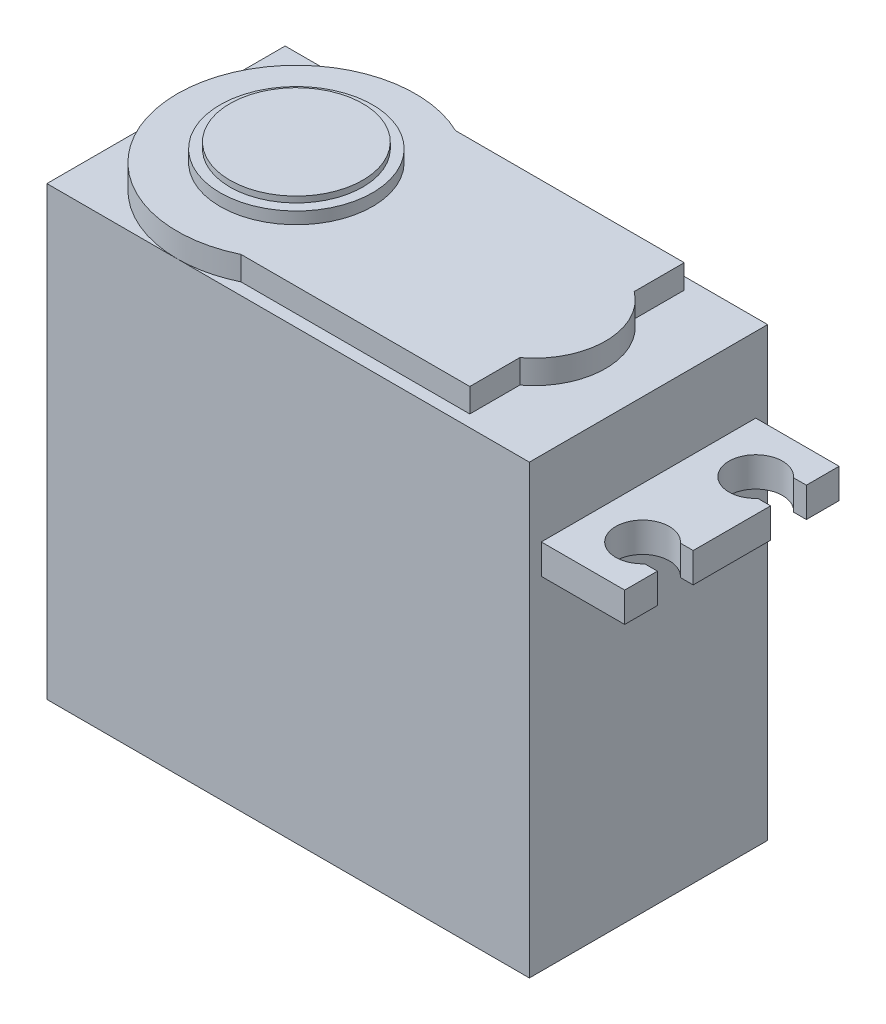
SolidWorks part; units mm, degrees
ref_plane "Front" through (0, 0, 0) normal (0, 0, 1) x (1, 0, 0)
ref_plane "Top" through (0, 0, 0) normal (0, 1, 0) x (1, 0, 0)
ref_plane "Right" through (0, 0, 0) normal (1, 0, 0) x (0, 0, -1)
sketch "Sketch1" plane through (0, 0, 0) normal (0, 1, 0) x (1, 0, 0)
  line L0 (-20.25, 10) -> (20.25, -10) construction
  line L1 (-20.25, -10) -> (20.25, -10)
  line L2 (-20.25, -10) -> (-20.25, 10)
  line L3 (-20.25, 10) -> (20.25, 10)
  line L4 (20.25, -10) -> (20.25, 10)
  line L5 (20.25, 10) -> (-20.25, -10) construction
  dimension "D1" = 20
  dimension "D2" = 40.5
extrude "Boss-Extrude1" add sketch "Sketch1" along normal blind 37.5
sketch "Sketch2" plane through (0, 37.5, 0) normal (0, 1, 0) x (1, 0, 0)
  line L0 (-4.95, -9) -> (14.25, -9)
  line L1 (14.25, -9) -> (14.25, -4.8)
  line L2 (-4.95, 9) -> (14.25, 9)
  line L3 (14.25, 9) -> (14.25, 4.8)
  line L4 (20.25, 10) -> (-20.25, 10) construction
  line L5 (-20.25, -10) -> (20.25, -10) construction
  line L6 (20.25, -10) -> (20.25, 10) construction
  line L7 (20.25, -10) -> (20.25, 10) construction
  arc A0 (-4.95, 9) -> (-4.95, -9) centre (-9.3089, 0) ccw
  arc A1 (14.25, 4.8) -> (14.25, -4.8) centre (10.65, 0) cw
  point P6 (0, 10)
  point P12 (16.65, 0)
  point P13 (20.25, 0)
  dimension "D1" = 1
  dimension "D3" = 4.2
  dimension "D2" = 1
  dimension "D4" = 3.6
  dimension "D5" = 19.2
  dimension "D6" = 6
extrude "Boss-Extrude2" add sketch "Sketch2" along normal blind 2
sketch "Sketch3" plane through (0, 39.5, 0) normal (0, 1, 0) x (1, 0, 0)
  circle A0 centre (-9.3089, 0) radius 6.4
  arc A1 (-9.3089, 10) -> (-9.3089, -10) centre (-9.3089, 0) ccw construction
  dimension "D1" = 12.8
extrude "Boss-Extrude3" add sketch "Sketch3" along normal blind 1
sketch "Sketch4" plane through (0, 40.5, 0) normal (0, 1, 0) x (1, 0, 0)
  circle A0 centre (-9.3089, 0) radius 5.575
  circle A1 centre (-9.3089, 0) radius 6.4 construction
  dimension "D1" = 11.15
extrude "Boss-Extrude4" add sketch "Sketch4" along normal blind 0.5
ref_plane "Plane1" through (0, 31.2, 0) normal (0, 1, 0) x (1, 0, 0)
sketch "Sketch5" plane through (0, 31.2, 0) normal (0, 1, 0) x (1, 0, 0)
  line L0 (20.25, 9) -> (27.25, 9)
  line L1 (20.25, -10) -> (20.25, 10) construction
  line L2 (27.25, 0) -> (27.25, 3.25)
  line L3 (20.25, 0) -> (27.25, 0)
  line L4 (20.25, 0) -> (20.25, 9)
  line L5 (20.25, 10) -> (-9.3089, 10) construction
  line L7 (24.5, 7) -> (24.5, 9) construction
  line L8 (27.25, 6.25) -> (27.25, 9)
  line L9 (26.1771, 6.25) -> (27.25, 6.25)
  line L10 (26.1771, 3.25) -> (27.25, 3.25)
  arc A0 (26.1771, 6.25) -> (26.1771, 3.25) centre (24.5, 4.75) ccw
  point P9 (22.25, 4.75)
  dimension "D4" = 4.5
  dimension "D5" = 2
  dimension "D1" = 1
  dimension "D2" = 9
  dimension "D3" = 7
  dimension "D6" = 3
  dimension "D7" = 2
extrude "Boss-Extrude5" add sketch "Sketch5" against normal blind 2.5
mirror "Mirror1" about plane through (0, 0, 0) normal (1, 0, 0) of "Boss-Extrude5"
mirror "Mirror2" about plane through (0, 0, 0) normal (0, 0, 1) of "Boss-Extrude5", "Mirror1"
sketch "ｽｹｯﾁ1" plane through (0, 0, 9) normal (0, 0, 1) x (1, 0, 0)
  line L1 (-20.25, 28.7) -> (-27.25, 28.7)
  line L2 (-20.25, 28.7) -> (-20.25, 31.2)
  line L3 (-20.25, 31.2) -> (-27.25, 31.2)
  line L4 (-27.25, 28.7) -> (-27.25, 31.2)
extrude "ｶｯﾄ - 押し出し1" cut sketch "ｽｹｯﾁ1" against normal through all
sketch "ｽｹｯﾁ2" plane through (0, 0, 9) normal (0, 0, 1) x (1, 0, 0)
  line L0 (11, 31.2) -> (-11, 31.2) construction
  line L1 (27.25, 28.7) -> (20.25, 28.7)
  line L2 (27.25, 28.7) -> (27.25, 31.2)
  line L3 (27.25, 31.2) -> (20.25, 31.2)
  line L4 (20.25, 28.7) -> (20.25, 31.2)
  line L5 (20.25, 37.5) -> (20.25, 0) construction
extrude "ｶｯﾄ - 押し出し2" [suppressed] cut sketch "ｽｹｯﾁ2" against normal through all
